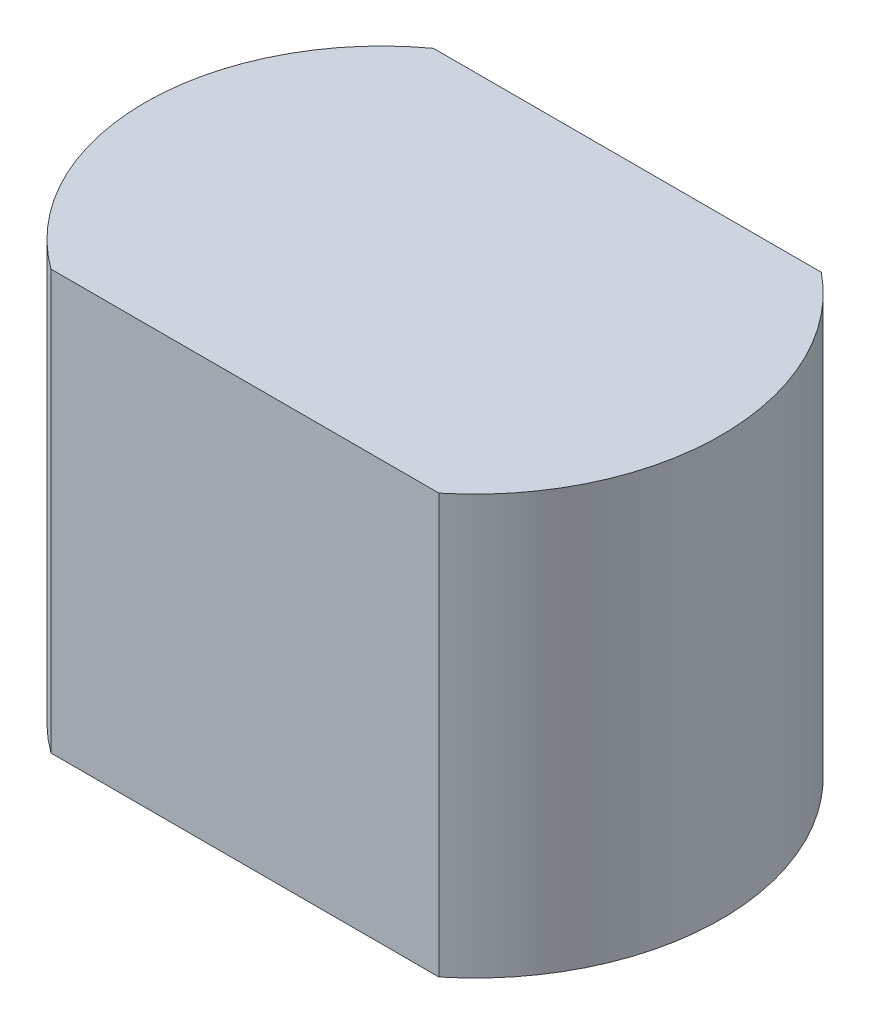
SolidWorks part; units mm, degrees
ref_plane "Front Plane" through (0, 0, 0) normal (0, 0, 1) x (1, 0, 0)
ref_plane "Top Plane" through (0, 0, 0) normal (0, 1, 0) x (1, 0, 0)
ref_plane "Right Plane" through (0, 0, 0) normal (1, 0, 0) x (0, 0, -1)
sketch "Sketch3" plane through (0, 0, 0) normal (0, 1, 0) x (1, 0, 0)
  line L0 (-5.099, 0.6788) -> (0.401, 0.6788) construction
  line L5 (-4.1709, 2.5038) -> (-0.4684, 2.5038)
  line L6 (-0.4684, 2.5038) -> (-0.4684, -1.1462) construction
  line L7 (-0.4684, -1.1462) -> (-4.1709, -1.1462)
  line L8 (-2.3196, 2.5038) -> (-2.3196, -1.1462) construction
  arc A0 (-4.1709, 2.5038) -> (-4.1709, -1.1462) centre (-2.8406, 0.6788) ccw
  arc A1 (-0.4684, 2.5038) -> (-0.4684, -1.1462) centre (-1.9491, 0.6788) cw
extrude "Boss-Extrude1" add sketch "Sketch3" along normal blind 4
sketch "Sketch4" plane through (0, 0, 0) normal (0, -1, 0) x (1, 0, 0)
  line L0 (-2.3196, 1.1462) -> (-2.3196, -2.5038)
  line L3 (-4.1709, 1.1462) -> (-0.4684, 1.1462) construction
  line L4 (-0.4684, -2.5038) -> (-4.1709, -2.5038) construction
  point P6 (-2.3196, -0.6788)
